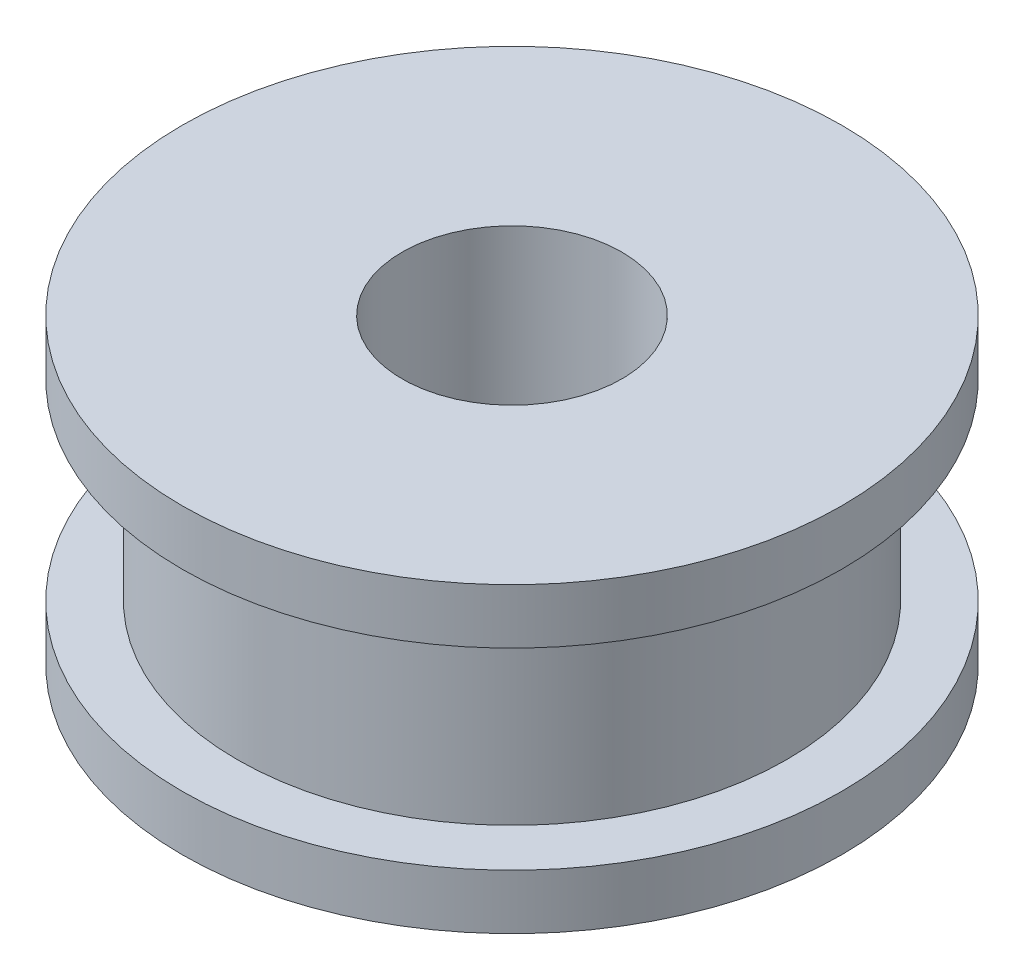
SolidWorks part; units mm, degrees
ref_plane "Front Plane" through (0, 0, 0) normal (0, 0, 1) x (1, 0, 0)
ref_plane "Top Plane" through (0, 0, 0) normal (0, 1, 0) x (1, 0, 0)
ref_plane "Right Plane" through (0, 0, 0) normal (1, 0, 0) x (0, 0, -1)
sketch "Sketch1" plane through (0, 0, 0) normal (0, 0, 1) x (1, 0, 0)
  line L0 (4, 11) -> (4, 0)
  line L1 (4, 0) -> (12, 0)
  line L2 (12, 0) -> (12, 2)
  line L3 (12, 2) -> (10, 2)
  line L4 (10, 2) -> (10, 9)
  line L5 (10, 9) -> (12, 9)
  line L6 (12, 9) -> (12, 11)
  line L7 (12, 11) -> (4, 11)
  line L8 (0, 0) -> (0, 13.8401) construction
  dimension "D1" = 7
  dimension "D2" = 12
  dimension "D3" = 10
  dimension "D4" = 11
  dimension "D5" = 4
revolve "Revolve1" add sketch "Sketch1" angle 360 about L8
